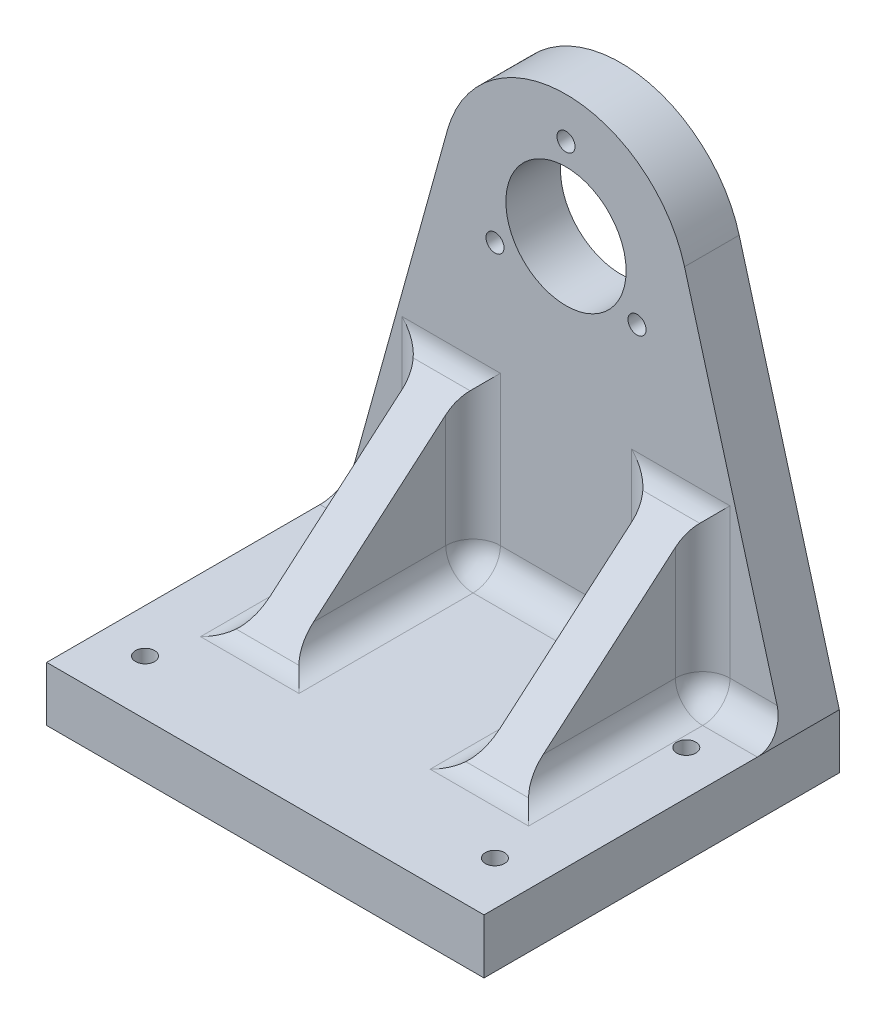
SolidWorks part; units mm, degrees
ref_plane "Front Plane" through (0, 0, 0) normal (0, 0, 1) x (1, 0, 0)
ref_plane "Top Plane" through (0, 0, 0) normal (0, 1, 0) x (1, 0, 0)
ref_plane "Right Plane" through (0, 0, 0) normal (1, 0, 0) x (0, 0, -1)
sketch "Sketch1" plane through (0, 0, 0) normal (0, 0, 1) x (1, 0, 0)
  line L0 (0, 20) -> (0, 15)
  line L1 (0, 0) -> (0, -60) construction
  line L2 (-40, -60) -> (40, -60)
  line L3 (40, -60) -> (21.6807, 6.0163)
  line L4 (-40, -60) -> (-21.6807, 6.0163)
  circle A0 centre (0, 0) radius 11
  circle A1 centre (0, 0) radius 20
  circle A2 centre (0, 15) radius 1.65
  circle A3 centre (0, 0) radius 11
  circle A4 centre (12.9904, -7.5) radius 1.65
  circle A5 centre (0, 0) radius 11
  circle A6 centre (-12.9904, -7.5) radius 1.65
  circle A7 centre (0, 0) radius 22.5
  point P15 (0, 0)
  point P18 (0, -60)
  dimension "D1" = 3
extrude "Boss-Extrude1" add sketch "Sketch1" against normal blind 10
sketch "Sketch2" plane through (0, -60, 0) normal (0, -1, 0) x (-1, 0, 0)
  line L1 (40, 0) -> (-40, 0)
  line L2 (40, 0) -> (40, 10)
  line L3 (40, 10) -> (-40, 10)
  line L4 (-40, 0) -> (-40, 10)
  line L5 (40, 0) -> (-40, 10) construction
  line L6 (40, 10) -> (-40, 0) construction
  point P4 (0, 5)
  dimension "D1" = 10
  dimension "D2" = 80
extrude "Boss-Extrude2" add sketch "Sketch2" along normal blind 10
sketch "Sketch3" plane through (0, 0, 0) normal (0, 0, 1) x (1, 0, 0)
  line L1 (-40, -70) -> (40, -70)
  line L2 (-40, -70) -> (-40, -60)
  line L3 (-40, -60) -> (40, -60)
  line L4 (40, -70) -> (40, -60)
  line L5 (-40, -70) -> (40, -60) construction
  line L6 (-40, -60) -> (40, -70) construction
  point P4 (0, -65)
  dimension "D1" = 10
  dimension "D2" = 80
extrude "Boss-Extrude3" add sketch "Sketch3" along normal blind 55
sketch "Sketch4" plane through (0, -60, 0) normal (0, 1, 0) x (1, 0, 0)
  line L0 (-40, 0) -> (-25, 0)
  line L1 (-40, 0) -> (40, 0)
  line L2 (-40, 0) -> (-40, -55)
  line L3 (-40, -55) -> (40, -55)
  line L4 (40, 0) -> (40, -55)
  line L5 (-40, 0) -> (40, -55) construction
  line L6 (-40, -55) -> (40, 0) construction
  line L7 (-25, 0) -> (-25, -35)
  line L8 (-25, -35) -> (-17, -35)
  line L9 (-17, -35) -> (-17, 0)
  line L10 (40, 0) -> (15, 0)
  line L11 (40, 0) -> (25, 0)
  line L12 (25, 0) -> (25, -35)
  line L13 (25, -35) -> (17, -35)
  line L14 (17, -35) -> (17, 0)
  point P4 (0, -27.5)
  dimension "D1" = 55
  dimension "D2" = 80
extrude "Boss-Extrude4" add sketch "Sketch4" along normal blind 30 contours L8 L9 L1 L7 | L14 L13 L12 L10
sketch "Sketch5" plane through (-25, 0, 0) normal (-1, 0, 0) x (0, 0, 1)
  line L0 (0, -30) -> (35, -60)
  line L1 (35, -30) -> (0, -30)
  line L2 (35, -30) -> (35, -60)
  line L3 (35, -60) -> (0, -60)
  line L4 (0, -30) -> (0, -60)
  line L5 (35, -30) -> (0, -60) construction
  line L6 (35, -60) -> (0, -30) construction
  point P4 (17.5, -45)
  line M2 (35, -60) -> (35, -30)
  line M3 (35, -30) -> (0, -30)
  dimension "D1" = 30
  dimension "D2" = 35
extrude "Cut-Extrude1" cut sketch "Sketch5" against normal blind 157 contours L0 M3 M2
sketch "Sketch6" plane through (0, -60, 0) normal (0, 1, 0) x (1, 0, 0)
  line L1 (-40, 0) -> (-32, 0)
  line L2 (-40, 0) -> (-40, -10)
  line L3 (-40, -10) -> (-32, -10)
  line L4 (-32, 0) -> (-32, -10)
  line L5 (-40, 0) -> (-32, -10) construction
  line L6 (-40, -10) -> (-32, 0) construction
  line L7 (40, 0) -> (32, 0)
  line L8 (40, 0) -> (40, -10)
  line L9 (40, -10) -> (32, -10)
  line L10 (32, 0) -> (32, -10)
  line L11 (40, 0) -> (32, -10) construction
  line L12 (40, -10) -> (32, 0) construction
  line L13 (40, -55) -> (32, -55)
  line L14 (40, -55) -> (40, -45)
  line L15 (40, -45) -> (32, -45)
  line L16 (32, -55) -> (32, -45)
  line L17 (40, -55) -> (32, -45) construction
  line L18 (40, -45) -> (32, -55) construction
  line L19 (-40, -55) -> (-32, -55)
  line L20 (-40, -55) -> (-40, -45)
  line L21 (-40, -45) -> (-32, -45)
  line L22 (-32, -55) -> (-32, -45)
  line L23 (-40, -55) -> (-32, -45) construction
  line L24 (-40, -45) -> (-32, -55) construction
  circle A1 centre (-32, -10) radius 1.75
  circle A2 centre (32, -10) radius 1.75
  circle A3 centre (32, -45) radius 1.75
  circle A4 centre (-32, -45) radius 1.75
  point P4 (-36, -5)
  point P9 (36, -5)
  point P14 (36, -50)
  point P19 (-36, -50)
  dimension "D1" = 10
  dimension "D2" = 8
  dimension "D3" = 10
  dimension "D4" = 8
  dimension "D5" = 10
  dimension "D6" = 8
  dimension "D7" = 10
  dimension "D8" = 8
extrude "Cut-Extrude2" cut sketch "Sketch6" against normal blind 157 contours L22 A4 L21 | L21 A4 L22 | L16 A3 L15 | L15 A3 L16 | L9 A2 L10 | L10 A2 L9 | L4 A1 L3 | L3 A1 L4
fillet "Fillet1" radius 5 15 edges at (21, -30, 0) (-21, -30, 0) (-25, -45, 0) (-17, -45, 0) (17, -45, 0) (25, -45, 0) (-25, -60, 17.5) (-21, -60, 35) (-17, -60, 17.5) (17, -60, 17.5) (21, -60, 35) (25, -60, 17.5) (32.5, -60, 0) (0, -60, 0) (-32.5, -60, 0)
